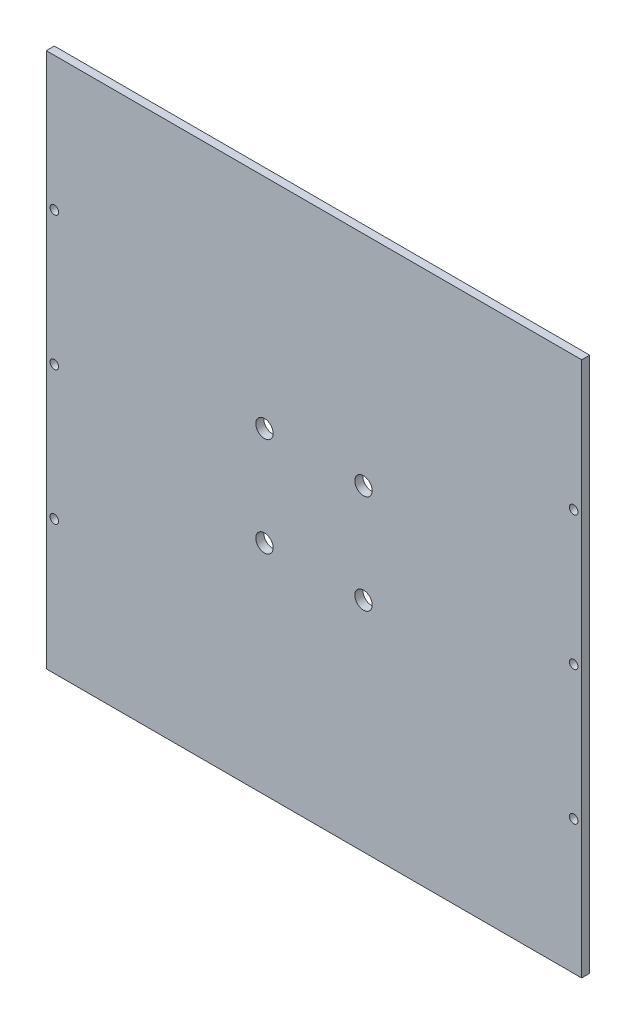
SolidWorks part; units mm, degrees
ref_plane "前视基准面" through (0, 0, 0) normal (0, 0, 1) x (1, 0, 0)
ref_plane "上视基准面" through (0, 0, 0) normal (0, 1, 0) x (1, 0, 0)
ref_plane "右视基准面" through (0, 0, 0) normal (1, 0, 0) x (0, 0, -1)
sketch "草图1" plane through (0, 0, 0) normal (0, 0, 1) x (1, 0, 0)
  line L0 (-80, 100) -> (-80, -100) construction
  line L1 (-100, 100) -> (100, 100)
  line L2 (-100, 100) -> (-100, -100)
  line L3 (-100, -100) -> (100, -100)
  line L4 (100, 100) -> (100, -100)
  line L5 (0, -100) -> (0, 100) construction
  line L6 (-100, 0) -> (100, 0) construction
  line L7 (-18.5, 18.5) -> (18.5, 18.5) construction
  line L8 (-18.5, 18.5) -> (-18.5, -18.5) construction
  line L9 (-18.5, -18.5) -> (18.5, -18.5) construction
  line L10 (18.5, 18.5) -> (18.5, -18.5) construction
  line L11 (0, -18.5) -> (0, 18.5) construction
  line L12 (-18.5, 0) -> (18.5, 0) construction
  circle A0 centre (-18.5, 18.5) radius 3.25
  circle A1 centre (18.5, 18.5) radius 3.25
  circle A2 centre (18.5, -18.5) radius 3.25
  circle A3 centre (-18.5, -18.5) radius 3.25
  circle A8 centre (97, -50) radius 1.6
  circle A9 centre (97, 50) radius 1.6
  circle A10 centre (-97, -50) radius 1.6
  circle A11 centre (-97, 50) radius 1.6
  circle A12 centre (-97, 0) radius 1.6
  circle A13 centre (97, 0) radius 1.6
  point P0 (0, 0)
  point P4 (0, 0)
  dimension "D5" = 6.5
  dimension "D7" = 3.2
  dimension "D9" = 3.2
  dimension "D4" = 37
  dimension "D8" = 3.2
  dimension "D1" = 200
  dimension "D2" = 200
  dimension "D3" = 37
  dimension "D6" = 61.5
  dimension "D10" = 3
extrude "凸台-拉伸1" add sketch "草图1" along normal blind 3
